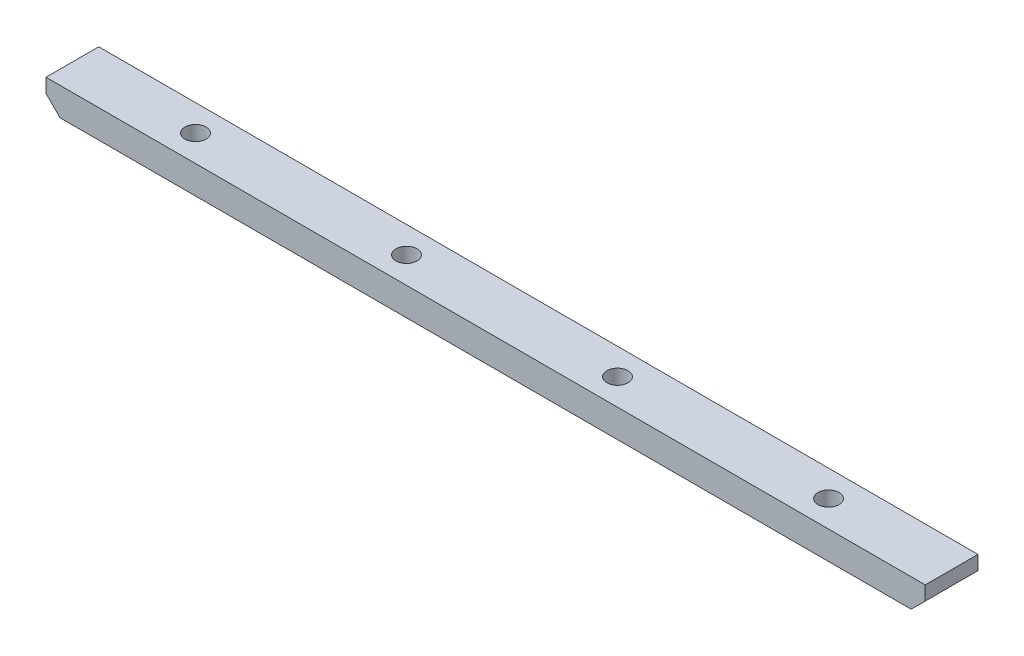
SolidWorks part; units mm, degrees
material "3.1355 (EN-AW 2024)"
ref_plane "Front" through (0, 0, 0) normal (0, 0, 1) x (1, 0, 0)
ref_plane "Top" through (0, 0, 0) normal (0, 1, 0) x (1, 0, 0)
ref_plane "Right" through (0, 0, 0) normal (1, 0, 0) x (0, 0, -1)
sketch "Эскиз2" plane through (0, 0, 0) normal (0, 0, 1) x (1, 0, 0)
  line L1 (-125, 4) -> (125, 4)
  line L2 (-125, 4) -> (-125, -4)
  line L3 (-125, -4) -> (125, -4)
  line L4 (125, 4) -> (125, -4)
  line L5 (-125, 4) -> (125, -4) construction
  line L6 (-125, -4) -> (125, 4) construction
  point P0 (0, 0)
  dimension "D1" = 8
  dimension "D2" = 250
extrude "База" add sketch "Эскиз2" against normal blind 15
hole_wizard "Отверстия-6мм" positions "Эскиз3" profile "Эскиз4" hole size "Ø6.0" standard "DIN" end condition through all
sketch "Эскиз3" plane through (0, 4, 0) normal (0, -1, 0) x (-1, 0, 0)
  line L17 (90, 7.5) -> (30, 7.5) construction
  line L18 (30, 7.5) -> (-30, 7.5) construction
  line L19 (-30, 7.5) -> (-90, 7.5) construction
  line L22 (0, 0) -> (0, 7.5) construction
  line L23 (0, 7.5) -> (0, 15) construction
  line L24 (-125, 15) -> (125, 15) construction
  point P4 (90, 7.5)
  point P8 (-90, 7.5)
  point P35 (30, 7.5)
  point P37 (-30, 7.5)
  point P55 (0, 7.5)
  dimension "D1" = 180
sketch "Эскиз4" plane through (-90, 4, -7.5) normal (1, 0, 0) x (0, 0, 1)
  line L0 (0, 0) -> (0, 8)
  line L1 (0, 8) -> (3, 8)
  line L2 (3, 8) -> (3, 0)
  line L5 (3, 0) -> (0, 0)
  line L11 (0, -6.35) -> (0, 107.95) construction
  dimension "Диаметр сквозного отверстия" = 6
  dimension "Глубина сквозного отверстия" = 8
chamfer "Фаска" distance 4 angle 45 2 edges at (125, -4, -7.5) (-125, -4, -7.5)
